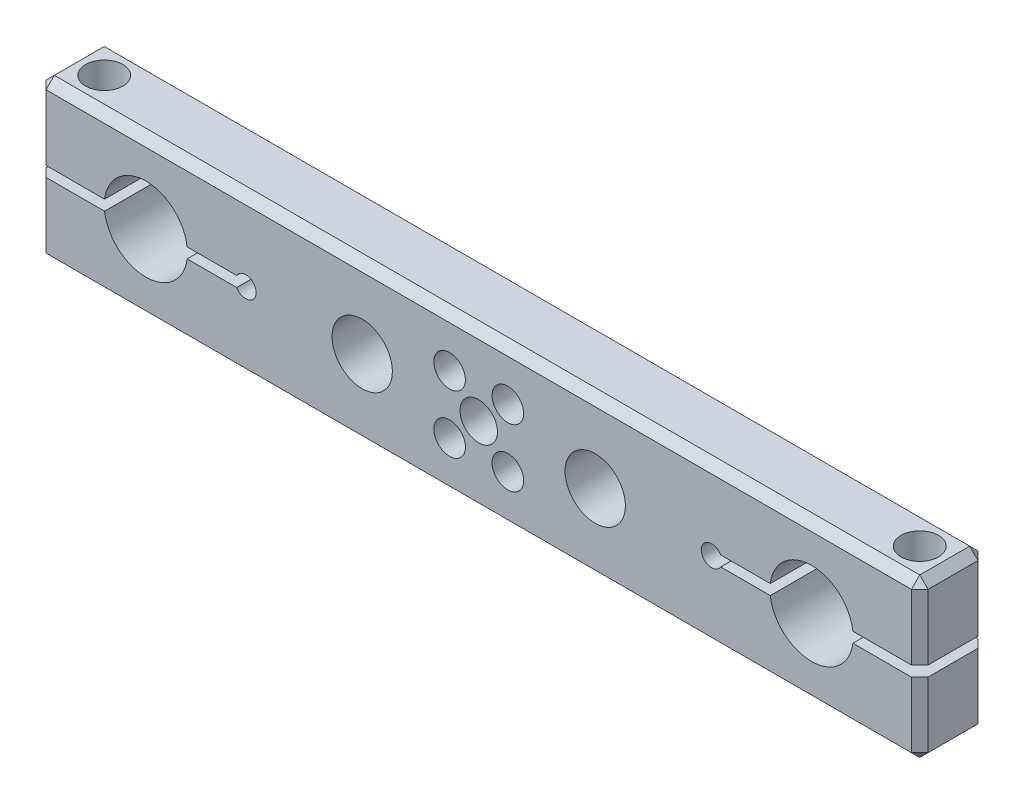
SolidWorks part; units mm, degrees
ref_plane "前视基准面" through (0, 0, 0) normal (0, 0, 1) x (1, 0, 0)
ref_plane "上视基准面" through (0, 0, 0) normal (0, 1, 0) x (1, 0, 0)
ref_plane "右视基准面" through (0, 0, 0) normal (1, 0, 0) x (0, 0, -1)
sketch "草图1" plane through (0, 0, 0) normal (0, 0, 1) x (1, 0, 0)
  line L0 (0, 0) -> (0, 53.8355) construction
  line L1 (-106, 19) -> (106, 19)
  line L2 (-106, 19) -> (-106, -19)
  line L3 (-106, -19) -> (106, -19)
  line L4 (106, 19) -> (106, -19)
  line L5 (0, 0) -> (116.9402, 0) construction
  dimension "D1" = 212
  dimension "D2" = 38
extrude "凸台-拉伸1" add sketch "草图1" along normal mid plane 16
sketch "草图2" plane through (0, 0, 8) normal (0, 0, 1) x (1, 0, 0)
  line L0 (0, 0) -> (0, 43.1784) construction
  line L1 (0, 0) -> (-80, 0) construction
  circle A0 centre (-80, 0) radius 10
  circle A1 centre (80, 0) radius 10
  dimension "D2" = 20
  dimension "D1" = 160
extrude "切除-拉伸1" cut sketch "草图2" against normal through all
sketch "草图3" plane through (0, 0, 8) normal (0, 0, 1) x (1, 0, 0)
  line L0 (-106, 19) -> (-106, -19) construction
  line L1 (-106, 1.25) -> (-56, 1.25)
  line L2 (-106, 1.25) -> (-106, -1.25)
  line L3 (-106, -1.25) -> (-56, -1.25)
  line L4 (-56, 1.25) -> (-56, -1.25)
  line L5 (0, 0) -> (0, 25.4721) construction
  line L6 (0, 0) -> (-126.0002, 0) construction
  line L7 (106, -1.25) -> (56, -1.25)
  line L8 (56, 1.25) -> (56, -1.25)
  line L9 (106, 1.25) -> (106, -1.25)
  line L10 (106, 1.25) -> (56, 1.25)
  dimension "D1" = 50
  dimension "D2" = 2.5
extrude "切除-拉伸2" cut sketch "草图3" against normal through all
sketch "草图4" plane through (0, 0, -8) normal (0, 0, 1) x (1, 0, 0)
  circle A0 centre (0, 0) radius 6
  dimension "D1" = 12
extrude "切除-拉伸3" cut sketch "草图4" along normal blind 4
sketch "草图5" plane through (0, 0, 8) normal (0, 0, 1) x (1, 0, 0)
  circle A0 centre (0, 0) radius 4.5
  dimension "D1" = 9
extrude "切除-拉伸4" cut sketch "草图5" against normal through all
hole_wizard "孔1" positions "草图7" profile "草图6" legacy end condition through all
sketch "草图7" plane through (0, 0, 8) normal (0, 0, 1) x (1, 0, 0)
  line L0 (0, 0) -> (0, 17.0282) construction
  line L2 (0, 0) -> (15.9247, 0) construction
  point P1 (-7, 7)
  point P3 (7, 7)
  point P5 (7, -7)
  point P7 (-7, -7)
  dimension "D1" = 14
  dimension "D2" = 14
sketch "草图6" plane through (-7, 7, 8) normal (1, 0, 0) x (0, -1, 0)
  line L0 (0, 0) -> (0, 16)
  line L1 (0, 16) -> (2.25, 16)
  line L2 (2.25, 16) -> (2.25, 10)
  line L3 (2.25, 10) -> (3.8, 10)
  line L4 (3.8, 10) -> (3.8, 0)
  line L5 (3.8, 0) -> (0, 0)
  line L6 (0, 110) -> (0, -10) construction
  dimension "直径" = 4.5
  dimension "深度" = 16
  dimension "柱坑直径" = 7.6
  dimension "柱坑深度" = 10
sketch "草图8" plane through (0, 0, 8) normal (0, 0, 1) x (1, 0, 0)
  line L0 (0, 0) -> (0, 33.3749) construction
  line L1 (0, 0) -> (-28, 0) construction
  circle A0 centre (-28, 0) radius 7.25
  circle A1 centre (28, 0) radius 7.25
  dimension "D2" = 14.5
  dimension "D1" = 56
extrude "切除-拉伸5" cut sketch "草图8" against normal through all
sketch "草图9" plane through (0, 19, 0) normal (0, 1, 0) x (1, 0, 0)
  line L0 (0, 0) -> (0, 21.3733) construction
  line L1 (0, 0) -> (-98, 0) construction
  circle A0 centre (-98, 0) radius 4.5
  circle A1 centre (98, 0) radius 4.5
  dimension "D2" = 9
  dimension "D1" = 196
extrude "切除-拉伸6" cut sketch "草图9" against normal up to surface (17.75 mm away) up to face at (97.9608, 1.25, 0)
hole_wizard "M8x1.25 螺纹孔1" positions "草图11" profile "草图12" tap size "M8x1.25" standard "JIS" end condition through all
sketch "草图11" plane through (0, -1.25, 0) normal (0, 1, 0) x (-1, 0, 0)
  point P1 (98, 0)
  point P8 (-98, 0)
sketch "草图12" plane through (-98, -1.25, 0) normal (1, 0, 0) x (0, 0, 1)
  line L0 (0, 0) -> (0, 17.75)
  line L1 (0, 17.75) -> (3.4, 17.75)
  line L2 (3.4, 17.75) -> (3.4, 0)
  line L5 (3.4, 0) -> (0, 0)
  line L11 (0, -6.35) -> (0, 107.95) construction
  dimension "通孔螺纹孔钻头直径" = 6.8
  dimension "通孔螺纹孔钻头深度" = 17.75
cosmetic thread "孔螺蚊线1" parameters "D2"=8
cosmetic thread "孔螺蚊线2" parameters "D2"=8
chamfer "倒角1" distance 2 angle 45 16 edges at (-106, -10.125, -8) (-106, -19, 0) (0, -19, -8) (0, -19, 8) (106, -10.125, -8) (106, -19, 0) (106, -10.125, 8) (-106, 10.125, 8) (-106, 19, 0) (-106, 10.125, -8) (0, 19, -8) (0, 19, 8) (106, 10.125, -8) (106, 10.125, 8) (106, 19, 0) (-106, -10.125, 8)
sketch "草图13" plane through (0, 0, 8) normal (0, 0, 1) x (1, 0, 0)
  line L0 (-56, -1.25) -> (-56, 1.25) construction
  line L1 (56, 1.25) -> (56, -1.25) construction
  circle A0 centre (-56, 0) radius 2.5
  circle A1 centre (56, 0) radius 2.5
  dimension "D1" = 5
extrude "切除-拉伸7" cut sketch "草图13" against normal through all
